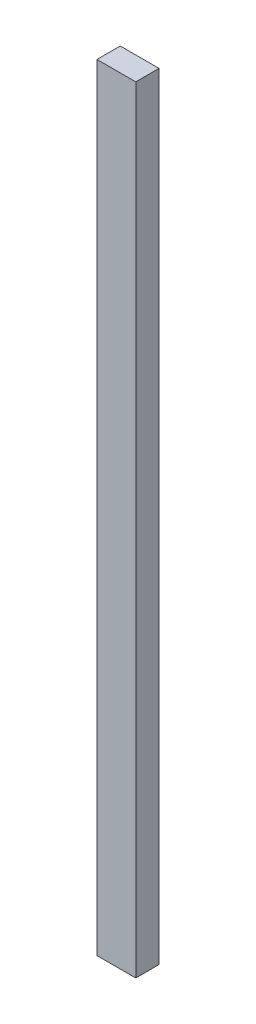
SolidWorks part; units mm, degrees
material "铸造合金钢"
ref_plane "前视基准面" through (0, 0, 0) normal (0, 0, 1) x (1, 0, 0)
ref_plane "上视基准面" through (0, 0, 0) normal (0, 1, 0) x (1, 0, 0)
ref_plane "右视基准面" through (0, 0, 0) normal (1, 0, 0) x (0, 0, -1)
sketch "草图1" plane through (0, 0, 0) normal (0, 1, 0) x (1, 0, 0)
  line L1 (-2.5, -1.5) -> (2.5, -1.5)
  line L2 (-2.5, -1.5) -> (-2.5, 1.5)
  line L3 (-2.5, 1.5) -> (2.5, 1.5)
  line L4 (2.5, -1.5) -> (2.5, 1.5)
  line L5 (0, 1.5) -> (0, -1.5) construction
  line L6 (-2.5, 0) -> (2.5, 0) construction
  point P0 (0, 0)
  dimension "D1" = 5
  dimension "D2" = 3
extrude "凸台-拉伸1" add sketch "草图1" along normal blind 100
